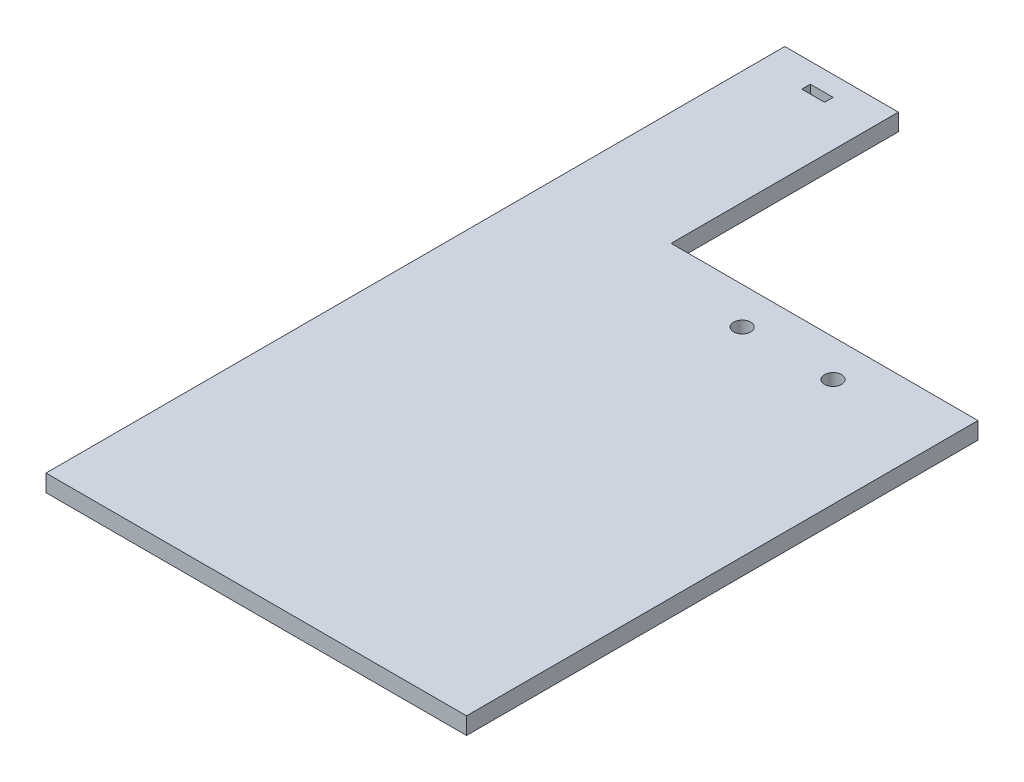
SolidWorks part; units mm, degrees
ref_plane "Front Plane" through (0, 0, 0) normal (0, 0, 1) x (1, 0, 0)
ref_plane "Top Plane" through (0, 0, 0) normal (0, 1, 0) x (1, 0, 0)
ref_plane "Right Plane" through (0, 0, 0) normal (1, 0, 0) x (0, 0, -1)
sketch "Sketch1" plane through (0, 0, 0) normal (0, 1, 0) x (1, 0, 0)
  line L0 (0, 90) -> (0, 130)
  line L1 (0, 0) -> (89, 0)
  line L2 (0, 0) -> (0, 90)
  line L4 (89, 0) -> (89, 90)
  line L5 (0, 130) -> (20, 130)
  line L7 (20, 130) -> (20, 90)
  line L8 (20, 90) -> (89, 90)
  line L10 (8, 126.5) -> (12, 126.5)
  line L11 (8, 126.5) -> (8, 125)
  line L12 (8, 125) -> (12, 125)
  line L13 (12, 126.5) -> (12, 125)
  dimension "D1" = 89
  dimension "D2" = 90
  dimension "D3" = 40
  dimension "D4" = 20
  dimension "D9" = 1.5
  dimension "D10" = 4
  dimension "D11" = 35
  dimension "D12" = 8
extrude "Boss-Extrude1" add sketch "Sketch1" along normal blind 3
sketch "Sketch3" [suppressed] plane through (0, 0, 0) normal (0, 0, 1) x (1, 0, 0)
  line L0 (0, 3) -> (89, 3) construction
  line L1 (89, 0) -> (86, 0)
  line L2 (89, 0) -> (89, 3)
  line L3 (89, 3) -> (86, 3)
  line L4 (86, 0) -> (86, 3)
  dimension "D1" = 3
extrude "Cut-Extrude2" [suppressed] cut sketch "Sketch3" against normal through all
sketch "Sketch4" plane through (0, 0, 0) normal (0, 0, 1) x (1, 0, 0)
  line L0 (0, 3) -> (89, 3) construction
  line L1 (89, 0) -> (74, 0)
  line L2 (89, 0) -> (89, 3)
  line L3 (89, 3) -> (74, 3)
  line L4 (74, 0) -> (74, 3)
  dimension "D1" = 15
extrude "Cut-Extrude3" cut sketch "Sketch4" against normal through all
sketch "Sketch5" [suppressed] plane through (0, 3, 0) normal (0, 1, 0) x (1, 0, 0)
  line L0 (46.5, 83.5) -> (62.5, 83.5) construction
  line L1 (89, 90) -> (20, 90) construction
  circle A0 centre (46.5, 83.5) radius 1.5
  circle A1 centre (62.5, 83.5) radius 1.5
  point P4 (54.5, 90)
  point P7 (54.5, 83.5)
  dimension "D1" = 3
  dimension "D2" = 3
  dimension "D3" = 16
  dimension "D4" = 6.5
sketch "Sketch6" [suppressed] plane through (0, 3, 0) normal (0, 1, 0) x (1, 0, 0)
  line L0 (45, 83.5) -> (61, 83.5) construction
  line L1 (86, 90) -> (20, 90) construction
  circle A0 centre (45, 83.5) radius 1.5
  circle A1 centre (61, 83.5) radius 1.5
  point P4 (53, 90)
  point P7 (53, 83.5)
  dimension "D1" = 3
  dimension "D2" = 3
  dimension "D3" = 16
  dimension "D4" = 6.5
sketch "Sketch7" plane through (0, 3, 0) normal (0, 1, 0) x (1, 0, 0)
  line L0 (39, 83.5) -> (55, 83.5) construction
  line L1 (74, 90) -> (20, 90) construction
  circle A0 centre (39, 83.5) radius 1.5
  circle A1 centre (55, 83.5) radius 1.5
  point P6 (47, 90)
  point P7 (47, 83.5)
  dimension "D1" = 3
  dimension "D2" = 3
  dimension "D3" = 16
  dimension "D4" = 6.5
extrude "Cut-Extrude4" [suppressed] cut sketch "Sketch5" against normal blind 10
extrude "Cut-Extrude5" [suppressed] cut sketch "Sketch6" against normal blind 10
extrude "Cut-Extrude6" cut sketch "Sketch7" against normal blind 10
